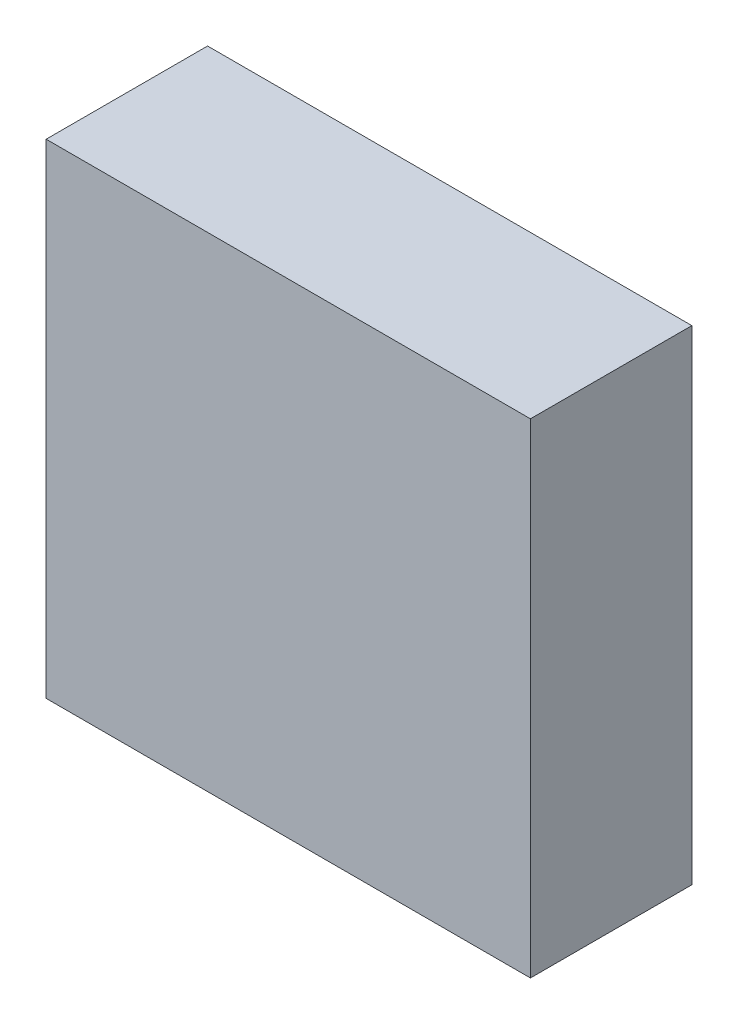
SolidWorks part; units mm, degrees
ref_plane "Front Plane" through (0, 0, 0) normal (0, 0, 1) x (1, 0, 0)
ref_plane "Top Plane" through (0, 0, 0) normal (0, 1, 0) x (1, 0, 0)
ref_plane "Right Plane" through (0, 0, 0) normal (1, 0, 0) x (0, 0, -1)
sketch "SK_Base" plane through (0, 0, 0) normal (0, 0, 1) x (1, 0, 0)
  line L1 (-15, -15) -> (15, -15)
  line L2 (-15, -15) -> (-15, 15)
  line L3 (-15, 15) -> (15, 15)
  line L4 (15, -15) -> (15, 15)
  line L5 (-15, -15) -> (15, 15) construction
  line L6 (-15, 15) -> (15, -15) construction
extrude "EX_Box" add sketch "SK_Base" along normal blind 10
